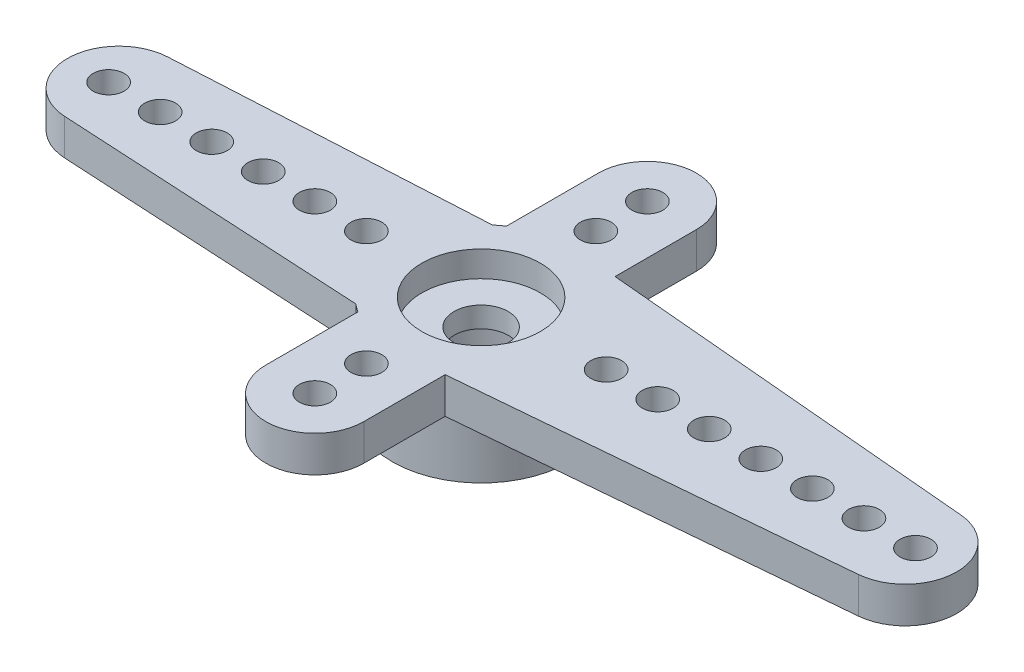
SolidWorks part; units mm, degrees
material "PVC Rígido"
ref_plane "Plano frontal" through (0, 0, 0) normal (0, 0, 1) x (1, 0, 0)
ref_plane "Plano superior" through (0, 0, 0) normal (0, 1, 0) x (1, 0, 0)
ref_plane "Plano direito" through (0, 0, 0) normal (1, 0, 0) x (0, 0, -1)
sketch "Esboço1" plane through (0, 0, 0) normal (0, 1, 0) x (1, 0, 0)
  line L0 (0, 0) -> (-14.05, 0) construction
  line L1 (-14.1591, 1.997) -> (-2.2091, 2.65)
  line L2 (-2.2091, -2.65) -> (-14.1591, -1.997)
  arc A0 (-2.2091, -2.65) -> (-2.2091, 2.65) centre (0, 0) ccw
  arc A1 (-14.1591, 1.997) -> (-14.1591, -1.997) centre (-14.05, 0) ccw
  dimension "D1" = 6.9
  dimension "D2" = 4
  dimension "D3" = 19.5
  dimension "D4" = 5.3
  dimension "D5" = 0.653
  dimension "D6" = 0.653
  dimension "D7" = 14.1591
  dimension "D8" = 3.994
extrude "Ressalto-extrusão1" add sketch "Esboço1" against normal blind 1.4
sketch "Esboço2" plane through (0, -1.4, 0) normal (0, -1, 0) x (1, 0, 0)
  arc A0 (-2.2091, -2.65) -> (-2.2091, 2.65) centre (0, 0) ccw construction
  circle A1 centre (0, 0) radius 3.45
extrude "Ressalto-extrusão2" add sketch "Esboço2" along normal offset from surface (2.4 mm away) 3.8 up to face at (-7.242, 0, 0)
hole_wizard "Furo1" positions "Esboço9" profile "Esboço10" legacy end condition through all
sketch "Esboço9" plane through (0, 0, 0) normal (0, 1, 0) x (1, 0, 0)
  line L1 (-14.45, 0) -> (0, 0) construction
  arc A2 (-14.1591, 1.997) -> (-14.1591, -1.997) centre (-14.05, 0) ccw construction
  point P0 (-14.45, 0)
  point P19 (-16.05, 0)
  dimension "D1" = 1.6
sketch "Esboço10" plane through (-14.45, 0, 0) normal (1, 0, 0) x (0, 0, 1)
  line L0 (0, 0) -> (0, 3.8)
  line L1 (0, 3.8) -> (0.6, 3.8)
  line L2 (0.6, 3.8) -> (0.6, 0)
  line L3 (0.6, 0) -> (0, 0)
  line L4 (0, 110) -> (0, -10) construction
  dimension "Diameter" = 1.2
  dimension "Depth" = 3.8
pattern_linear "Padrão linear1" count 6 spacing 2 along (1, 0, 0) of "Furo1"
sketch "Esboço12" plane through (0, 0, 0) normal (0, 1, 0) x (1, 0, 0)
  line L0 (0.3041, 3.4366) -> (16.6263, 1.9922)
  line L1 (16.6263, -1.9922) -> (0.3041, -3.4366)
  arc A0 (-2.2091, -2.65) -> (-2.2091, 2.65) centre (0, 0) ccw construction
  arc A1 (0.3041, -3.4366) -> (0.3041, 3.4366) centre (0, 0) ccw
  arc A2 (16.6263, 1.9922) -> (16.6263, -1.9922) centre (16.45, 0) cw
  arc A3 (-14.1591, 1.997) -> (-14.1591, -1.997) centre (-14.05, 0) ccw construction
  dimension "D1" = 2
  dimension "D2" = 34.5
extrude "Ressalto-extrusão3" add sketch "Esboço12" against normal up to surface (1.4 mm away) up to face at (-12.45, -1.4, 0.6)
hole_wizard "Furo2" positions "Esboço13" profile "Esboço14" legacy end condition through all
sketch "Esboço13" plane through (0, 0, 0) normal (0, 1, 0) x (1, 0, 0)
  line L0 (0, 0) -> (16.85, 0) construction
  arc A0 (16.6263, -1.9922) -> (16.6263, 1.9922) centre (16.45, 0) ccw construction
  point P0 (16.85, 0)
  point P6 (18.45, 0)
  dimension "D1" = 1.6
sketch "Esboço14" plane through (16.85, 0, 0) normal (1, 0, 0) x (0, 0, 1)
  line L0 (0, 0) -> (0, 3.8)
  line L1 (0, 3.8) -> (0.6, 3.8)
  line L2 (0.6, 3.8) -> (0.6, 0)
  line L3 (0.6, 0) -> (0, 0)
  line L4 (0, 110) -> (0, -10) construction
  dimension "Diameter" = 1.2
  dimension "Depth" = 3.8
pattern_linear "Padrão linear2" count 7 spacing 2 along (-1, 0, 0) of "Furo2"
sketch "Esboço16" plane through (0, 0, 0) normal (0, 1, 0) x (1, 0, 0)
  line L0 (0, -6.45) -> (0, 6.45) construction
  line L1 (-1.9, -6.45) -> (-1.9, 6.45)
  line L2 (1.9, -6.45) -> (1.9, 6.45)
  arc A0 (-1.9, -6.45) -> (1.9, -6.45) centre (0, -6.45) ccw
  arc A1 (1.9, 6.45) -> (-1.9, 6.45) centre (0, 6.45) ccw
  point P2 (0, 0)
  dimension "D2" = 16.7
  dimension "D1" = 3.8
extrude "Ressalto-extrusão4" add sketch "Esboço16" against normal up to surface (1.4 mm away) up to face at (14.85, -1.4, 0.6)
hole_wizard "Furo3" positions "Esboço17" profile "Esboço18" legacy end condition through all
sketch "Esboço17" plane through (0, 0, 0) normal (0, 1, 0) x (1, 0, 0)
  point P0 (0, -6.45)
sketch "Esboço18" plane through (0, 0, 6.45) normal (1, 0, 0) x (0, 0, 1)
  line L0 (0, 0) -> (0, 3.8)
  line L1 (0, 3.8) -> (0.6, 3.8)
  line L2 (0.6, 3.8) -> (0.6, 0)
  line L3 (0.6, 0) -> (0, 0)
  line L4 (0, 110) -> (0, -10) construction
  dimension "Diameter" = 1.2
  dimension "Depth" = 3.8
pattern_linear "Padrão linear3" count 2 spacing 2 along (0, 0, -1) of "Furo3"
pattern_circular "PadrãoCircular1" count 2 over 360 about axis through (0, 0, 0) along (0, 1, 0) of "Padrão linear3", "Furo3"
hole_wizard "Furo4" positions "Esboço3" profile "Esboço4" legacy
sketch "Esboço3" plane through (0, -3.8, 0) normal (0, -1, 0) x (-1, 0, 0)
  point P0 (0, 0)
sketch "Esboço4" plane through (0, -3.8, 0) normal (1, 0, 0) x (0, 0, -1)
  line L0 (0, 0) -> (0, 2)
  line L1 (0, 2) -> (2.5, 2)
  line L2 (2.5, 2) -> (2.5, 0)
  line L3 (2.5, 0) -> (0, 0)
  line L4 (0, 110) -> (0, -10) construction
  dimension "Diameter" = 5
  dimension "Depth" = 2
hole_wizard "Furo5" positions "Esboço5" profile "Esboço6" legacy
sketch "Esboço5" plane through (0, 0, 0) normal (0, 1, 0) x (1, 0, 0)
  point P0 (0, 0)
sketch "Esboço6" plane through (0, 0, 0) normal (1, 0, 0) x (0, 0, 1)
  line L0 (0, 0) -> (0, 1)
  line L1 (0, 1) -> (2.3, 1)
  line L2 (2.3, 1) -> (2.3, 0)
  line L3 (2.3, 0) -> (0, 0)
  line L4 (0, 110) -> (0, -10) construction
  dimension "Diameter" = 4.6
  dimension "Depth" = 1
hole_wizard "Furo6" positions "Esboço7" profile "Esboço8" legacy end condition through all
sketch "Esboço7" plane through (0, 0, 0) normal (0, 1, 0) x (1, 0, 0)
  point P0 (0, 0)
sketch "Esboço8" plane through (0, 0, 0) normal (1, 0, 0) x (0, 0, 1)
  line L0 (0, 0) -> (0, 3.8)
  line L1 (0, 3.8) -> (1.05, 3.8)
  line L2 (1.05, 3.8) -> (1.05, 0)
  line L3 (1.05, 0) -> (0, 0)
  line L4 (0, 110) -> (0, -10) construction
  dimension "Diameter" = 2.1
  dimension "Depth" = 3.8
